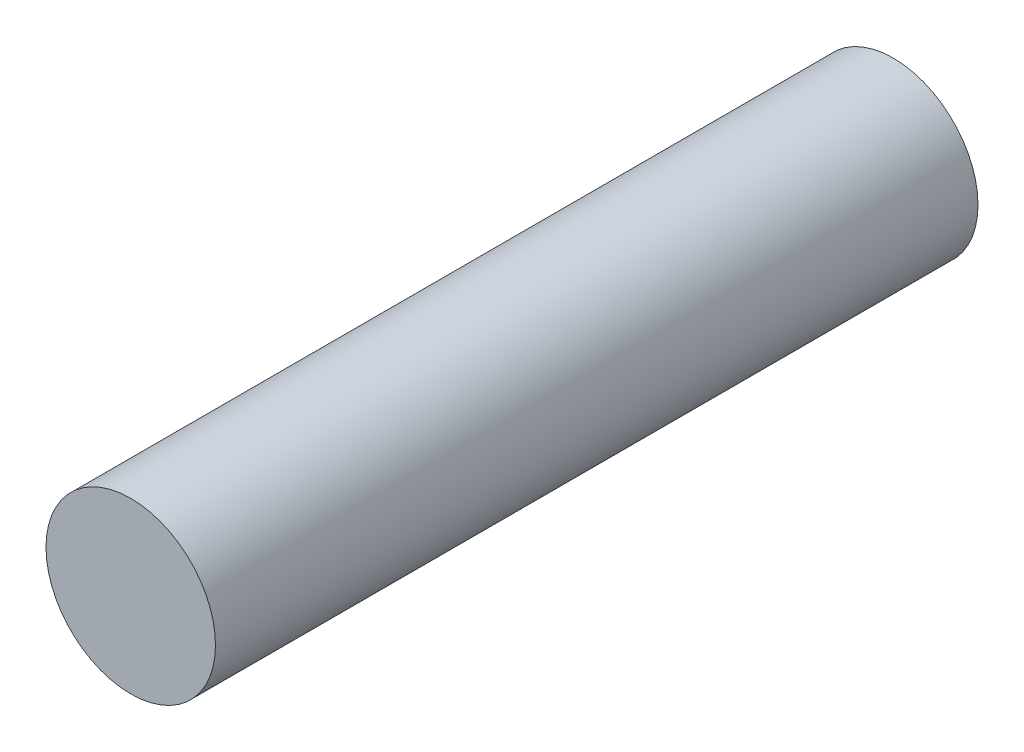
SolidWorks part; units mm, degrees
ref_plane "前视基准面" through (0, 0, 0) normal (0, 0, 1) x (1, 0, 0)
ref_plane "上视基准面" through (0, 0, 0) normal (0, 1, 0) x (1, 0, 0)
ref_plane "右视基准面" through (0, 0, 0) normal (1, 0, 0) x (0, 0, -1)
other "Configuration Table"
sketch "草图1" plane through (0, 0, 0) normal (1, 0, 0) x (0, 0, -1)
  line L0 (0, 0) -> (0, 20)
  line L1 (0, 20) -> (180, 20)
  line L2 (180, 20) -> (180, 0)
  line L3 (180, 0) -> (0, 0)
  line L4 (0, 0) -> (180, 0) construction
revolve "旋转1" add sketch "草图1" angle 360 about L4
